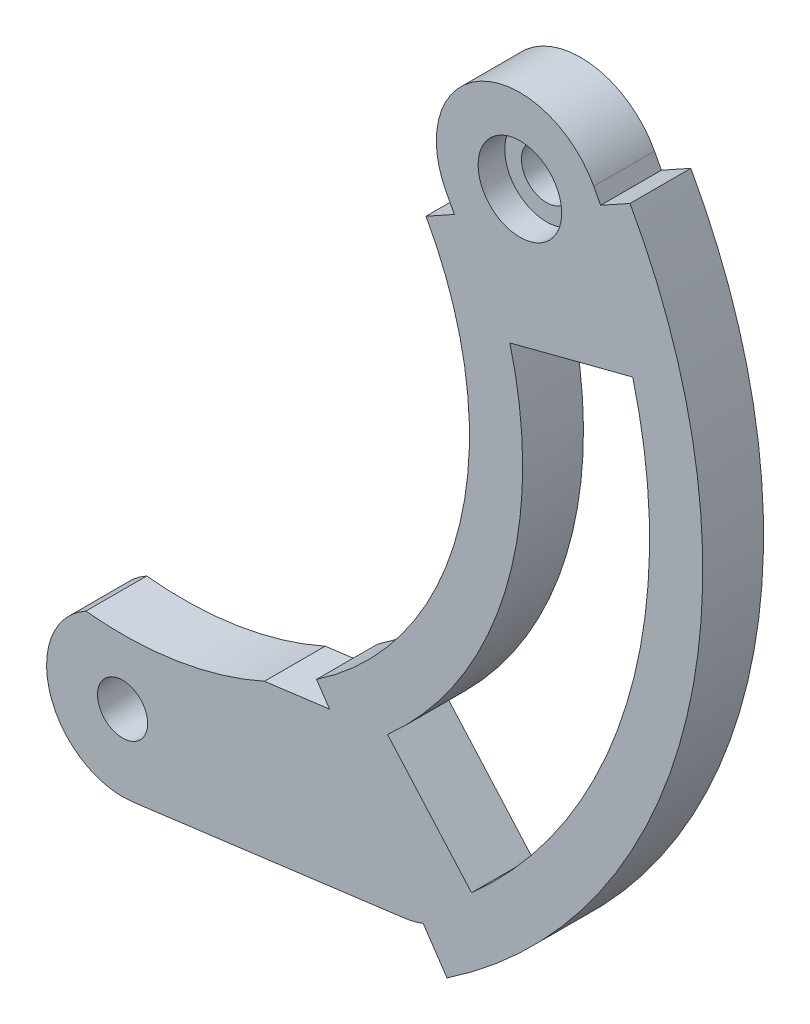
SolidWorks part; units mm, degrees
ref_plane "Front Plane" through (0, 0, 0) normal (0, 0, 1) x (1, 0, 0)
ref_plane "Top Plane" through (0, 0, 0) normal (0, 1, 0) x (1, 0, 0)
ref_plane "Right Plane" through (0, 0, 0) normal (1, 0, 0) x (0, 0, -1)
sketch "S01 - Eight millimetre track blank" plane through (0, 0, 0) normal (0, 0, 1) x (1, 0, 0)
  line L0 (25.5272, -37.8456) -> (42.6944, -63.297)
  line L1 (66.7772, 37.0152) -> (39.9264, 22.1316)
  arc A0 (42.6944, -63.297) -> (66.7772, 37.0152) centre (0, 0) ccw
  arc A1 (39.9264, 22.1316) -> (25.5272, -37.8456) centre (0, 0) cw
  dimension "D1" = 76.35
  dimension "D2" = 45.65
  dimension "D3" = 25.5272
  dimension "D4" = 39.9264
  dimension "D5" = 42.6944
  dimension "D6" = 66.7772
extrude "01 - Eight millimetre track blank" add sketch "S01 - Eight millimetre track blank" along normal blind 8
sketch "S02 - Lower cage tie landing" plane through (0, 0, 0) normal (0, 0, 1) x (1, 0, 0)
  line L0 (-1.2861, -44.083) -> (34.5688, -39.4331)
  line L1 (37.141, -59.267) -> (1.2861, -63.917)
  arc A0 (34.5688, -39.4331) -> (37.141, -59.267) centre (35.8549, -49.35) cw
  arc A1 (1.2861, -63.917) -> (-1.2861, -44.083) centre (0, -54) cw
  dimension "D1" = 10
  dimension "D2" = 10
  dimension "D3" = 1.2861
  dimension "D4" = 34.5688
  dimension "D5" = 35.8549
  dimension "D6" = 37.141
  dimension "D7" = 1.2861
  dimension "D8" = 39.4331
  dimension "D9" = 44.083
extrude "02 - Lower cage tie landing" add sketch "S02 - Lower cage tie landing" along normal blind 8
sketch "S03 - Bump end support landing" plane through (0, 0, 0) normal (0, 0, 1) x (1, 0, 0)
  line L0 (45.5724, 20.6155) -> (42.5748, 26.2531)
  line L1 (61.9996, 36.5815) -> (64.9972, 30.9439)
  arc A0 (42.5748, 26.2531) -> (61.9996, 36.5815) centre (52.2872, 31.4173) cw
  arc A1 (64.9972, 30.9439) -> (45.5724, 20.6155) centre (55.2848, 25.7797) cw
  dimension "D1" = 11
  dimension "D2" = 11
  dimension "D3" = 42.5748
  dimension "D4" = 45.5724
  dimension "D5" = 52.2872
  dimension "D6" = 55.2848
  dimension "D7" = 61.9996
  dimension "D8" = 64.9972
  dimension "D9" = 20.6155
  dimension "D10" = 26.2531
extrude "03 - Bump end support landing" add sketch "S03 - Bump end support landing" along normal blind 8
sketch "S04 - Relief for the swept floating guide barrels" plane through (0, 0, 0) normal (0, 0, 1) x (1, 0, 0)
  circle A0 centre (0, 0) radius 45.5
  dimension "D1" = 91
extrude "04 - Relief for the swept floating guide barrels" cut sketch "S04 - Relief for the swept floating guide barrels" along normal blind 8.2 from offset 0.1 offset against normal yes
sketch "S05 - Concentric guide and tangent stop faces" plane through (0, 0, 0) normal (0, 0, 1) x (1, 0, 0)
  line L0 (34.8622, -39.4544) -> (45.9201, -51.9689)
  line L1 (67.1301, 17.4059) -> (50.9647, 13.2145)
  arc A0 (45.9201, -51.9689) -> (67.1301, 17.4059) centre (0, 0) ccw
  arc A1 (50.9647, 13.2145) -> (34.8622, -39.4544) centre (0, 0) cw
  dimension "D1" = 69.35
  dimension "D2" = 52.65
  dimension "D3" = 34.8622
  dimension "D4" = 45.9201
  dimension "D5" = 50.9647
  dimension "D6" = 67.1301
extrude "05 - Concentric guide and tangent stop faces" cut sketch "S05 - Concentric guide and tangent stop faces" along normal blind 8.2 from offset 0.1 offset against normal yes
sketch "S06 - Support fasteners" plane through (0, 0, 0) normal (0, 0, 1) x (1, 0, 0)
  circle A0 centre (0, -54) radius 3.3
  circle A1 centre (52.2872, 31.4173) radius 3.3
  dimension "D1" = 6.6
  dimension "D2" = 6.6
  dimension "D3" = 52.2872
  dimension "D4" = 31.4173
  dimension "D5" = 54
extrude "06 - Support fasteners" cut sketch "S06 - Support fasteners" along normal blind 8.2 from offset 0.1 offset against normal yes
sketch "S07 - Bump end support register underside" plane through (0, 0, 0) normal (0, 0, 1) x (1, 0, 0)
  circle A0 centre (52.2872, 31.4173) radius 5.06
  dimension "D1" = 10.12
  dimension "D2" = 52.2872
  dimension "D3" = 31.4173
extrude "07 - Bump end support register underside" cut sketch "S07 - Bump end support register underside" along normal blind 1.35 from offset 0.1 offset against normal yes
sketch "S08 - Flush button screw counterbore outboard" plane through (0, 0, 0) normal (0, 0, 1) x (1, 0, 0)
  circle A0 centre (52.2872, 31.4173) radius 5.5
  dimension "D1" = 11
  dimension "D2" = 52.2872
  dimension "D3" = 31.4173
extrude "08 - Flush button screw counterbore outboard" cut sketch "S08 - Flush button screw counterbore outboard" along normal blind 3.6 from offset 4.5
